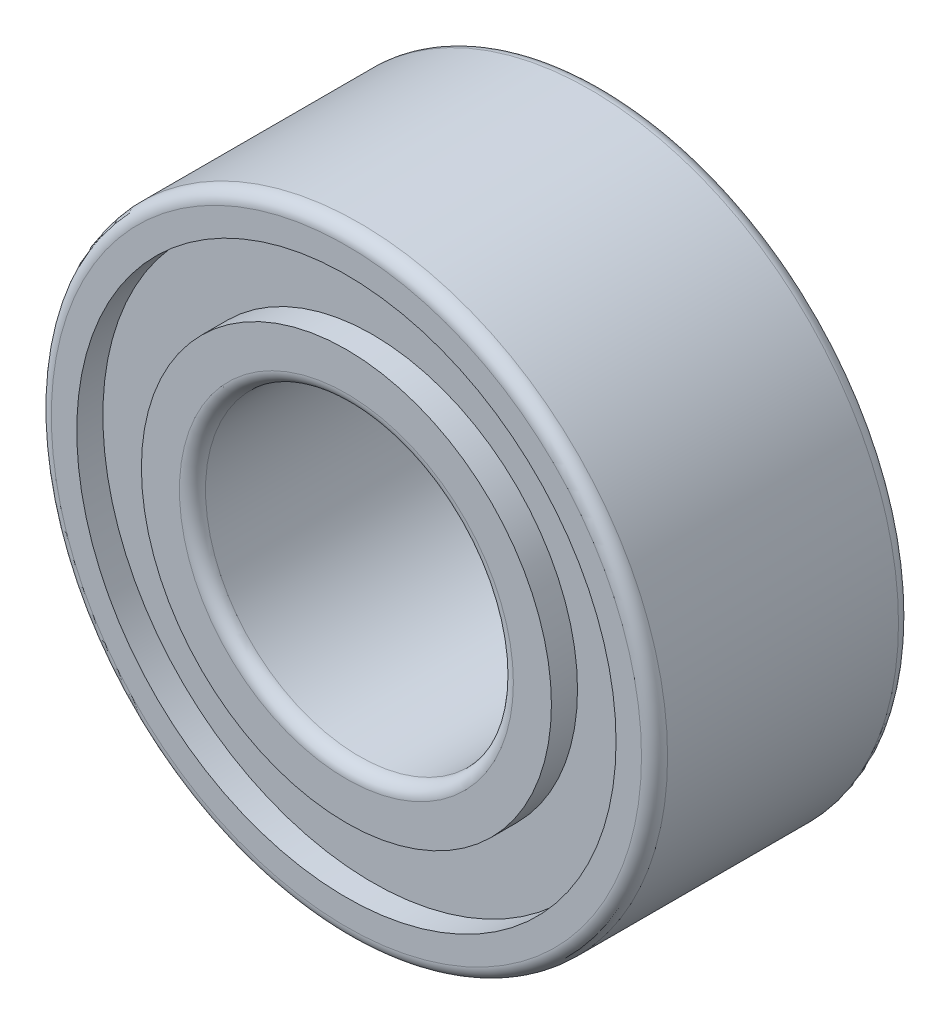
SolidWorks part; units mm, degrees
ref_plane "Front Plane" through (0, 0, 0) normal (0, 0, 1) x (1, 0, 0)
ref_plane "Top Plane" through (0, 0, 0) normal (0, 1, 0) x (1, 0, 0)
ref_plane "Right Plane" through (0, 0, 0) normal (1, 0, 0) x (0, 0, -1)
sketch "Sketch1" plane through (0, 0, 0) normal (0, 0, 1) x (1, 0, 0)
  circle A0 centre (0, 0) radius 1.4986
  circle A1 centre (0, 0) radius 2.9997
  dimension "D1" = 2.9972
  dimension "D2" = 5.9995
extrude "Extrude1" add sketch "Sketch1" along normal blind 2.5019
fillet "Fillet1" radius 0.127 4 edges at (2.9997, 0, 0) (1.4986, 0, 0) (1.4986, 0, 2.5019) (2.9997, 0, 2.5019)
sketch "Sketch2" plane through (0, 0, 2.5019) normal (0, 0, 1) x (1, 0, 0)
  circle A0 centre (0, 0) radius 1.9959
  circle A1 centre (0, 0) radius 2.6251
  dimension "D1" = 5.2502
  dimension "D2" = 3.9917
extrude "Cut-Extrude1" cut sketch "Sketch2" against normal blind 0.254
sketch "Sketch3" plane through (0, 0, 0) normal (0, 0, -1) x (-1, 0, 0)
  circle A0 centre (0, 0) radius 1.9939
  circle A1 centre (0, 0) radius 2.6251
extrude "Cut-Extrude2" cut sketch "Sketch3" against normal blind 0.254
